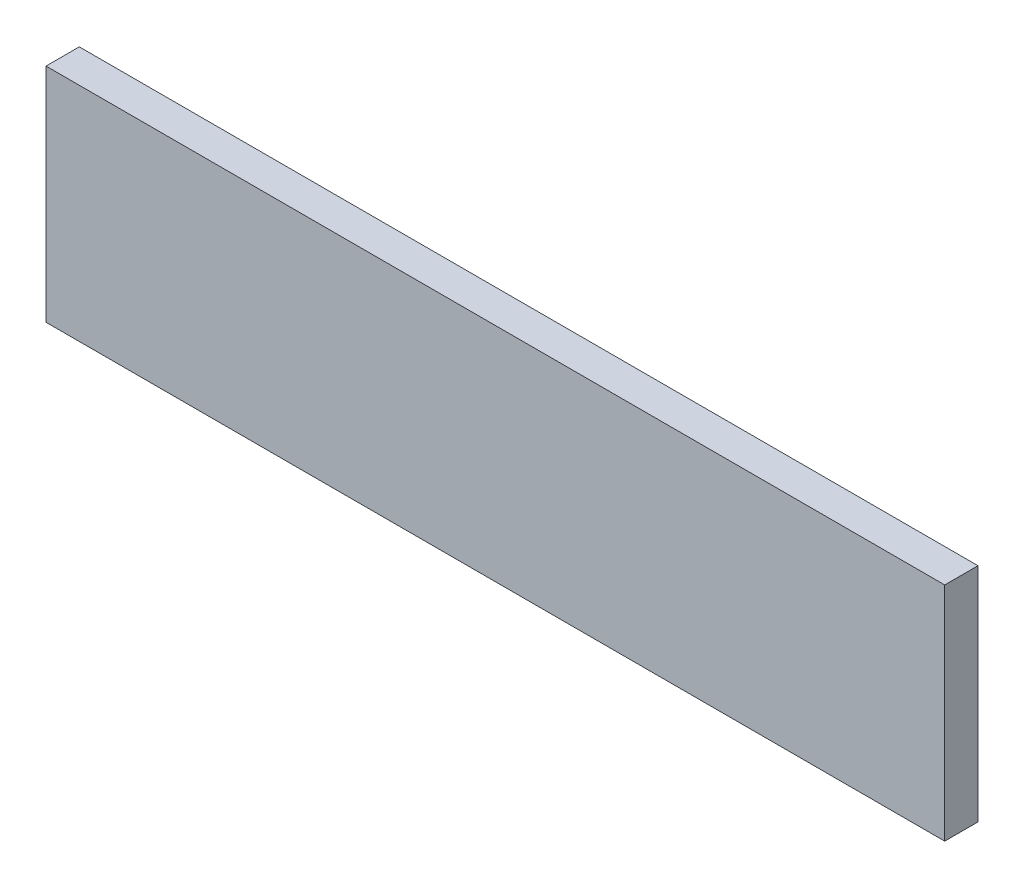
SolidWorks part; units mm, degrees
ref_plane "Front Plane" through (0, 0, 0) normal (0, 0, 1) x (1, 0, 0)
ref_plane "Top Plane" through (0, 0, 0) normal (0, 1, 0) x (1, 0, 0)
ref_plane "Right Plane" through (0, 0, 0) normal (1, 0, 0) x (0, 0, -1)
sketch "Sketch1" plane through (0, 0, 0) normal (0, 0, 1) x (1, 0, 0)
  line L1 (0, 0) -> (514.35, 0)
  line L2 (0, 0) -> (0, 127)
  line L3 (0, 127) -> (514.35, 127)
  line L4 (514.35, 0) -> (514.35, 127)
  line L5 (0, 0) -> (514.35, 127) construction
  line L6 (0, 127) -> (514.35, 0) construction
  point P4 (257.175, 63.5)
  dimension "D1" = 127
  dimension "D2" = 514.35
extrude "Boss-Extrude1" add sketch "Sketch1" along normal blind 19.05 contours L3 L4 L1 L2
